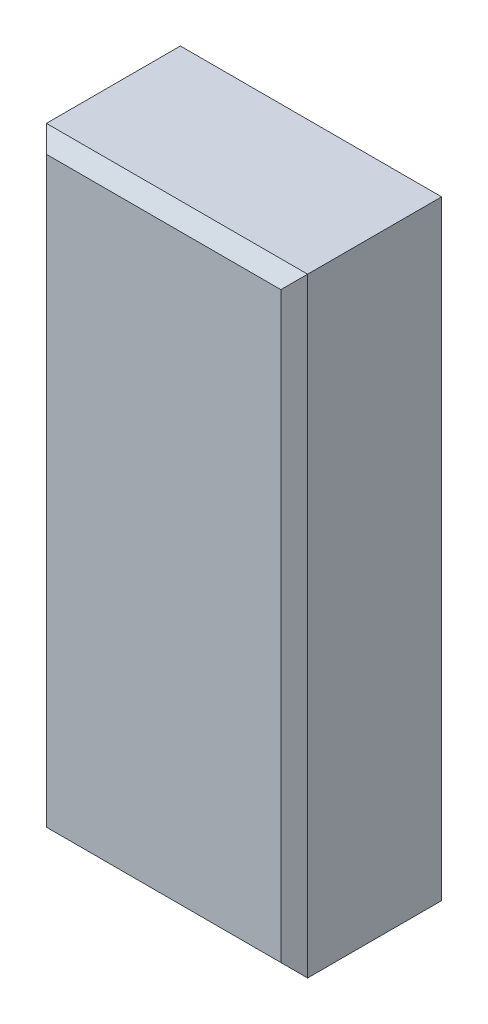
SolidWorks part; units mm, degrees
ref_plane "Front Plane" through (0, 0, 0) normal (0, 0, 1) x (1, 0, 0)
ref_plane "Top Plane" through (0, 0, 0) normal (0, 1, 0) x (1, 0, 0)
ref_plane "Right Plane" through (0, 0, 0) normal (1, 0, 0) x (0, 0, -1)
sketch "Sketch1" plane through (0, 0, 0) normal (0, 0, 1) x (1, 0, 0)
  line L1 (-9.75, 22.75) -> (9.75, 22.75)
  line L2 (-9.75, 22.75) -> (-9.75, -22.75)
  line L3 (-9.75, -22.75) -> (9.75, -22.75)
  line L4 (9.75, 22.75) -> (9.75, -22.75)
  line L5 (-9.75, 22.75) -> (9.75, -22.75) construction
  line L6 (-9.75, -22.75) -> (9.75, 22.75) construction
  point P0 (0, 0)
  dimension "D1" = 19.5
  dimension "D2" = 45.5
extrude "Boss-Extrude1" add sketch "Sketch1" along normal blind 11
chamfer "Chamfer1" distance 1 angle 45 4 edges at (0, -22.75, 11) (-9.75, 0, 11) (0, 22.75, 11) (9.75, 0, 11)
equation "\"thiccnes\"=9.5"
equation "\"D1@Boss-Extrude1\"=\"thiccnes\""
